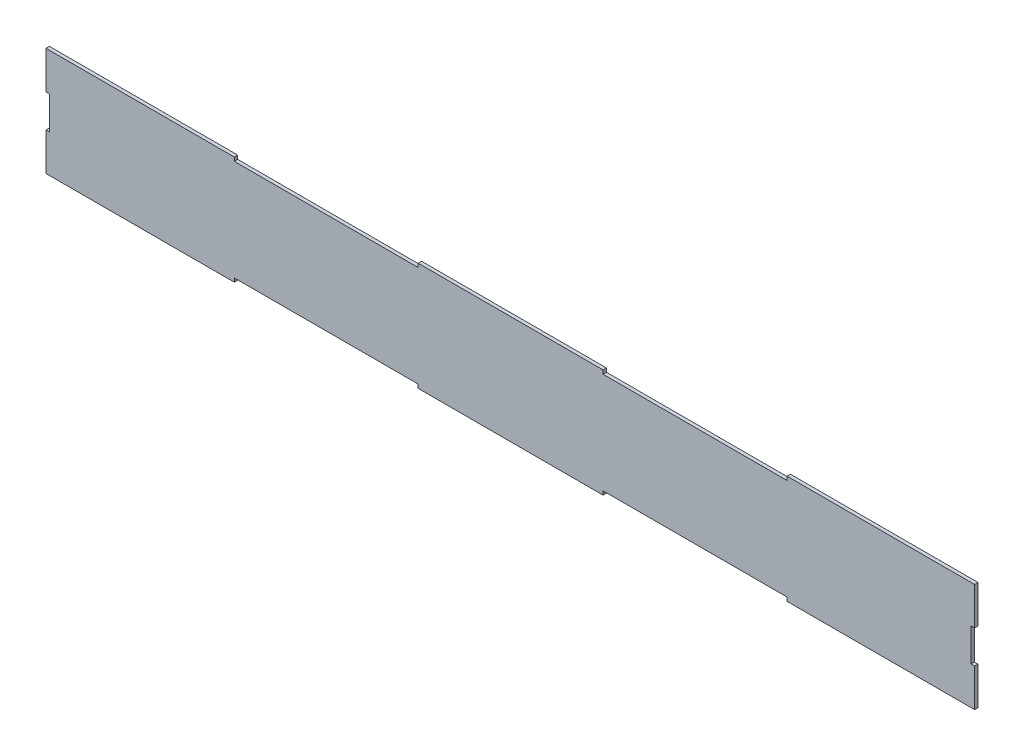
SolidWorks part; units mm, degrees
ref_plane "Front Plane" through (0, 0, 0) normal (0, 0, 1) x (1, 0, 0)
ref_plane "Top Plane" through (0, 0, 0) normal (0, 1, 0) x (1, 0, 0)
ref_plane "Right Plane" through (0, 0, 0) normal (1, 0, 0) x (0, 0, -1)
sketch "Sketch1" plane through (0, 0, 0) normal (0, 0, 1) x (1, 0, 0)
  line L0 (-43.3333, 0) -> (-129.84, 0)
  line L1 (130.16, 0) -> (43.6533, 0)
  line L2 (216.6667, 15.9933) -> (216.6667, 23.75)
  line L3 (216.6667, 23.75) -> (-216.6667, 23.75)
  line L4 (-216.6667, 15.9933) -> (-216.6667, 23.75)
  line L7 (-216.6667, -1.76) -> (-218.4267, -1.76)
  line L8 (-218.4267, 0) -> (-218.4267, -1.76)
  line L11 (-216.6667, 15.9933) -> (-218.4267, 15.9933)
  line L12 (-218.4267, 0) -> (-218.4267, 15.9933)
  line L15 (-216.6667, -1.76) -> (-129.84, -1.76)
  line L16 (-129.84, 0) -> (-129.84, -1.76)
  line L18 (-43.3333, 0) -> (-43.3333, -1.76)
  line L19 (-43.3333, -1.76) -> (43.6533, -1.76)
  line L20 (43.6533, 0) -> (43.6533, -1.76)
  line L22 (130.16, 0) -> (130.16, -1.76)
  line L23 (130.16, -1.76) -> (216.6667, -1.76)
  line L25 (216.6667, -1.76) -> (218.4267, -1.76)
  line L28 (218.4267, -1.76) -> (218.4267, 0)
  line L30 (218.4267, 0) -> (218.4267, 15.9933)
  line L31 (218.4267, 15.9933) -> (216.6667, 15.9933)
  point P3 (0, 23.75)
  dimension "D1" = 1.76
  dimension "D2" = 15.9933
  dimension "D3" = 23.75
  dimension "D4" = 433.3333
  dimension "D5" = 86.8267
  dimension "D6" = 86.9867
  dimension "D7" = 86.5067
extrude "Boss-Extrude1" add sketch "Sketch1" along normal blind 1.6
mirror "Mirror1" about plane through (216.6667, 23.75, 1.6) normal (0, -1, 0) of "Boss-Extrude1"
equation "\"thinkness\"= \"epaisseur\""
equation "\"hauteur\"= 47.5"
equation "\"largeur\"= \"nbCarre\" * \"Coté\""
equation "\"longueur\"= \"nbCarre\" * \"Coté\""
equation "\"D1@Sketch1\" = \"thinkness\" + \"jeu\""
equation "\"D2@Sketch1\" = \"hauteur\" / 3 + \"jeu\""
equation "\"D4@Sketch1\"= \"largeur\""
equation "\"D3@Sketch1\" = \"hauteur\" / 2"
equation "\"D1@Boss-Extrude1\"= \"thinkness\""
equation "\"jeu\"= 0.16"
equation "\"D5@Sketch1\" = \"largeur\" / 5 + \"jeu\""
equation "\"D7@Sketch1\"= \"largeur\" / 5 - \"jeu\""
equation "\"D6@Sketch1\" = \"largeur\" / 5 + \"jeu\" * 2"
equation "\"Coté\"= 33.333333"
equation "\"nbCarre\"= 13"
equation "\"epaisseur\"= 1.6"
equation "\"rapportEncoche\"= 0.5"
